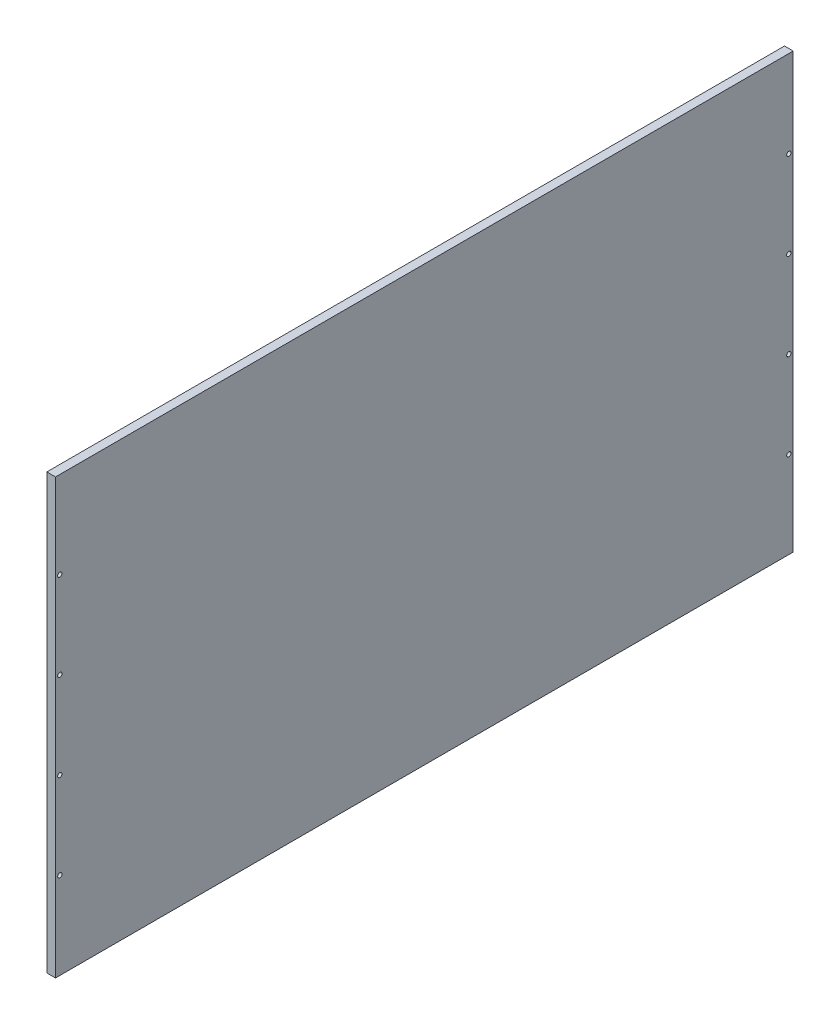
SolidWorks part; units mm, degrees
ref_plane "Alzado" through (0, 0, 0) normal (0, 0, 1) x (1, 0, 0)
ref_plane "Planta" through (0, 0, 0) normal (0, 1, 0) x (1, 0, 0)
ref_plane "Vista lateral" through (0, 0, 0) normal (1, 0, 0) x (0, 0, -1)
sketch "Croquis1" plane through (0, 0, 0) normal (1, 0, 0) x (0, 0, -1)
  line L1 (-425, -250) -> (425, -250)
  line L2 (-425, -250) -> (-425, 250)
  line L3 (-425, 250) -> (425, 250)
  line L4 (425, -250) -> (425, 250)
  line L5 (-425, -250) -> (425, 250) construction
  line L6 (-425, 250) -> (425, -250) construction
  point P0 (0, 0)
  dimension "D1" = 850
  dimension "D2" = 500
extrude "Saliente-Extruir1" add sketch "Croquis1" along normal mid plane 10
sketch "Croquis3" plane through (0, -250, 0) normal (0, -1, 0) x (1, 0, 0)
  line L0 (0, 425) -> (0, -425) construction
  line L1 (5, 425) -> (-5, 425) construction
  line L2 (5, -425) -> (-5, -425) construction
  circle A0 centre (0, -375) radius 2.5
  circle A1 centre (0, -275) radius 2.5
  circle A2 centre (0, -175) radius 2.5
  circle A3 centre (0, -75) radius 2.5
  circle A4 centre (0, 25) radius 2.5
  circle A5 centre (0, 125) radius 2.5
  circle A6 centre (0, 225) radius 2.5
  circle A7 centre (0, 325) radius 2.5
  dimension "D1" = 5
  dimension "D2" = 50
  dimension "D3" = 8
extrude "Cortar-Extruir1" cut sketch "Croquis3" against normal blind 5
sketch "Croquis5" plane through (5, 0, 0) normal (1, 0, 0) x (0, 0, -1)
  line L0 (-420, 278.481) -> (-420, -306.5417) construction
  line L1 (-425, 250) -> (-425, -250) construction
  line L2 (-425, -250) -> (425, -250) construction
  line L3 (0, 287.0897) -> (0, -278.7571) construction
  circle A0 centre (-420, -150) radius 2.5
  circle A1 centre (-420, -50) radius 2.5
  circle A2 centre (-420, 50) radius 2.5
  circle A3 centre (-420, 150) radius 2.5
  circle A4 centre (420, 150) radius 2.5
  circle A5 centre (420, 50) radius 2.5
  circle A6 centre (420, -50) radius 2.5
  circle A7 centre (420, -150) radius 2.5
  dimension "D2" = 5
  dimension "D1" = 5
  dimension "D3" = 100
  dimension "D4" = 4
extrude "Cortar-Extruir3" cut sketch "Croquis5" against normal blind 5
